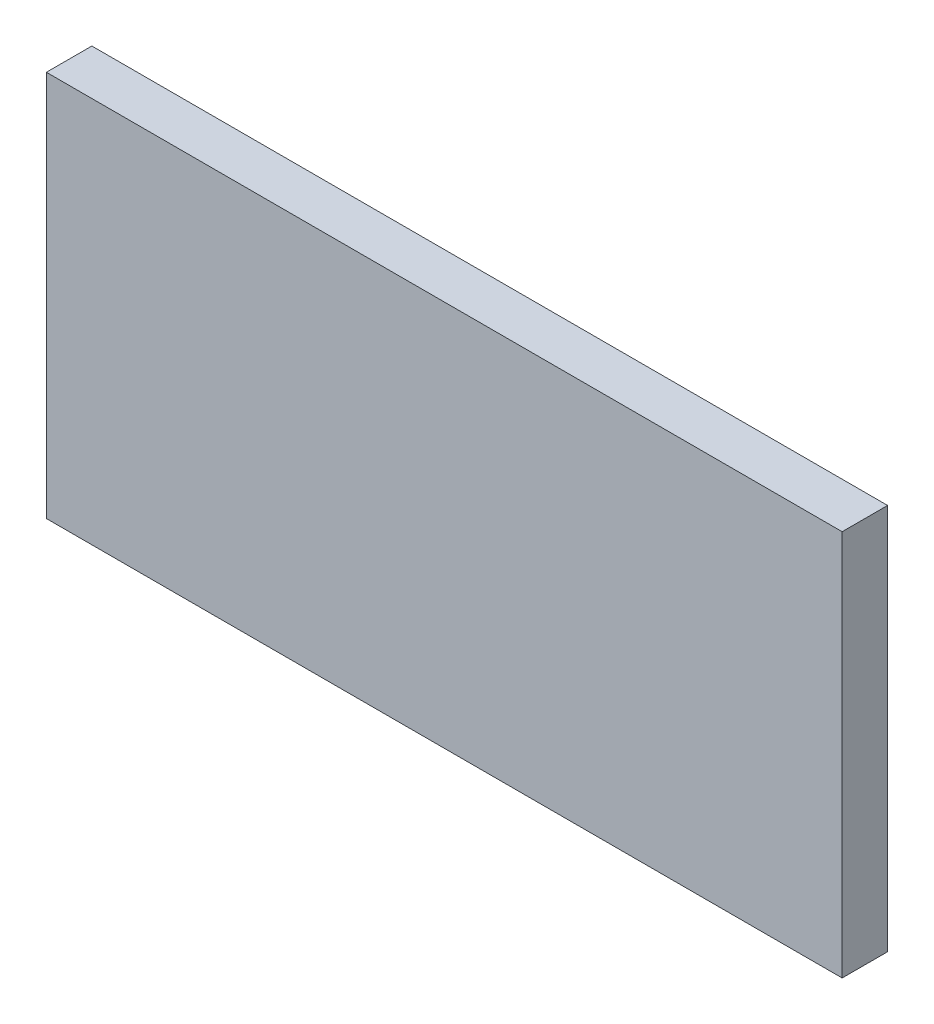
SolidWorks part; units mm, degrees
material "Клен"
ref_plane "Спереди" through (0, 0, 0) normal (0, 0, 1) x (1, 0, 0)
ref_plane "Сверху" through (0, 0, 0) normal (0, 1, 0) x (1, 0, 0)
ref_plane "Справа" through (0, 0, 0) normal (1, 0, 0) x (0, 0, -1)
sketch "Эскиз1" plane through (0, 0, 0) normal (0, 0, 1) x (1, 0, 0)
  line L0 (0, 0) -> (0, -400) construction
  line L1 (0, 0) -> (350, 0)
  line L2 (0, 0) -> (0, 170)
  line L3 (0, 170) -> (350, 170)
  line L4 (350, 0) -> (350, 170)
  line L5 (310, -400) -> (90, -400) construction
  dimension "D1" = 350
  dimension "D2" = 400
  dimension "D3" = 170
extrude "Бобышка-Вытянуть1" add sketch "Эскиз1" along normal blind 20
